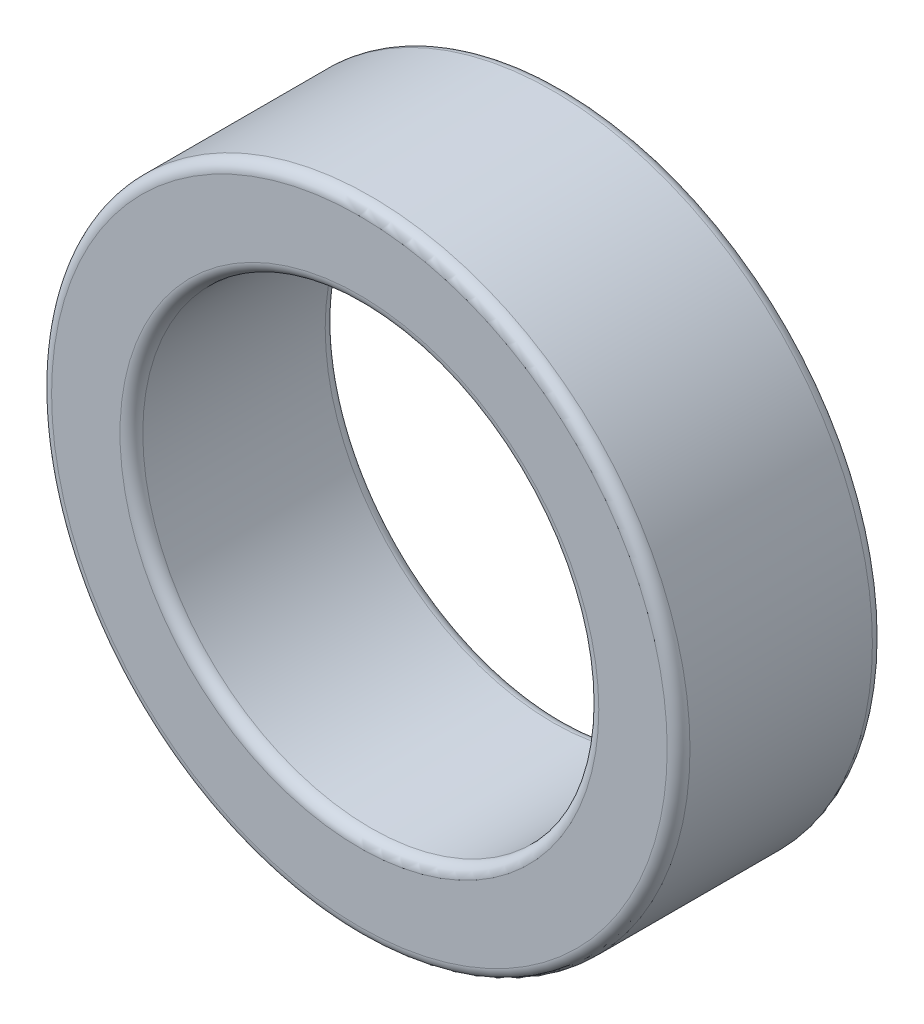
SolidWorks part; units mm, degrees
material "Plain Carbon Steel"
ref_plane "Front Plane" through (0, 0, 0) normal (0, 0, 1) x (1, 0, 0)
ref_plane "Top Plane" through (0, 0, 0) normal (0, 1, 0) x (1, 0, 0)
ref_plane "Right Plane" through (0, 0, 0) normal (1, 0, 0) x (0, 0, -1)
sketch "Sketch1" plane through (0, 0, 0) normal (0, 0, 1) x (1, 0, 0)
  circle A0 centre (0, 0) radius 7
  circle A1 centre (0, 0) radius 5
  dimension "D1" = 10
  dimension "D2" = 14
extrude "Boss-Extrude1" add sketch "Sketch1" along normal mid plane 4.5
fillet "Fillet1" radius 0.25 4 edges at (5, 0, -2.25) (5, 0, 2.25) (7, 0, -2.25) (7, 0, 2.25)
